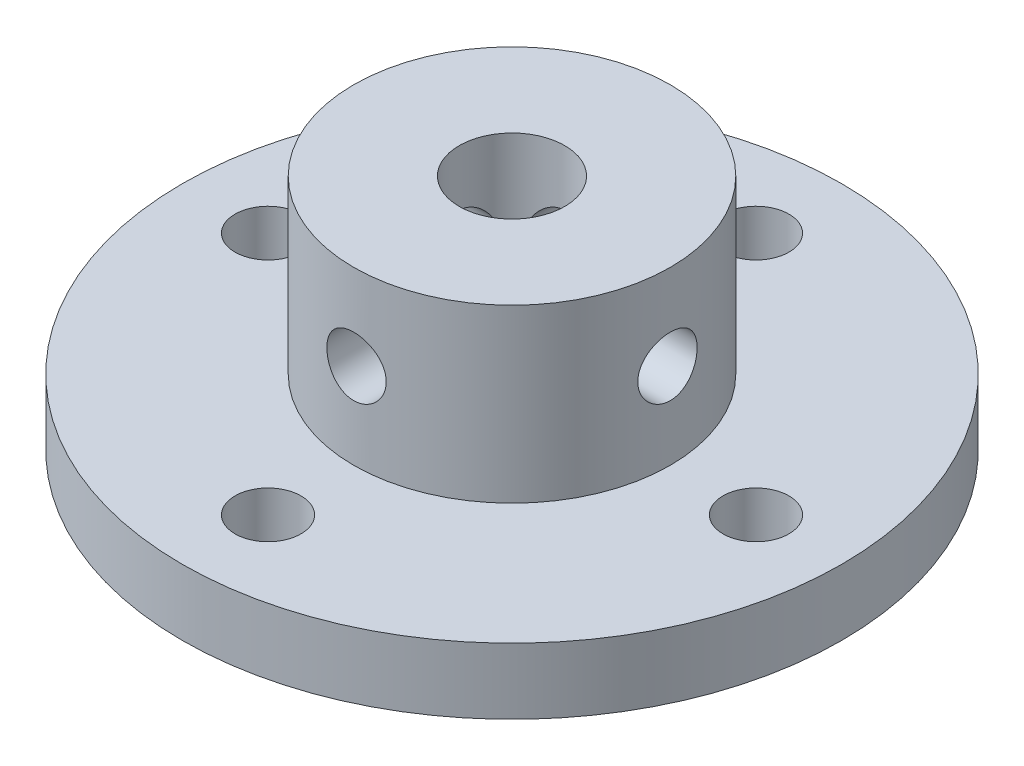
SolidWorks part; units mm, degrees
ref_plane "前视基准面" through (0, 0, 0) normal (0, 0, 1) x (1, 0, 0)
ref_plane "上视基准面" through (0, 0, 0) normal (0, 1, 0) x (1, 0, 0)
ref_plane "右视基准面" through (0, 0, 0) normal (1, 0, 0) x (0, 0, -1)
other "Configuration Table"
sketch "草图1" plane through (0, 0, 0) normal (0, 1, 0) x (1, 0, 0)
  circle A0 centre (0, 0) radius 25
  dimension "D1" = 50
extrude "凸台-拉伸1" add sketch "草图1" along normal blind 5
sketch "草图2" plane through (0, 5, 0) normal (0, 1, 0) x (1, 0, 0)
  circle A0 centre (0, 0) radius 12
  dimension "D1" = 24
extrude "凸台-拉伸2" add sketch "草图2" along normal blind 13
sketch "草图3" plane through (0, 18, 0) normal (0, 1, 0) x (1, 0, 0)
  circle A0 centre (0, 0) radius 4
  dimension "D1" = 8
extrude "切除-拉伸1" cut sketch "草图3" against normal through all
sketch "草图4" plane through (0, 5, 0) normal (0, 1, 0) x (1, 0, 0)
  circle A0 centre (0, 0) radius 18.5
  circle A1 centre (0, 18.5) radius 2.5
  circle A2 centre (18.5, 0) radius 2.5
  circle A3 centre (0, -18.5) radius 2.5
  circle A4 centre (-18.5, 0) radius 2.5
  dimension "D1" = 37
  dimension "D2" = 5
  dimension "D3" = 5
  dimension "D4" = 5
  dimension "D5" = 5
extrude "切除-拉伸2" cut sketch "草图4" against normal through all contours A0 A1 | A0 A1 | A0 A2 | A0 A2 | A0 A3 | A0 A3 | A0 A4 | A0 A4
sketch "草图5" plane through (0, 0, 0) normal (1, 0, 0) x (0, 0, -1)
  line L0 (0, 9.9) -> (0, -9.9) construction
  line L1 (12, 18) -> (-12, 18) construction
  circle A0 centre (0, 11.5) radius 2.25
  dimension "D1" = 4.5
  dimension "D2" = 6.5
extrude "切除-拉伸3" cut sketch "草图5" against normal through all and the other way through all
cosmetic thread "装饰螺纹线2" parameters "D2"=5.5
cosmetic thread "装饰螺纹线4" parameters "D2"=5.5
sketch "草图6" plane through (0, 0, 0) normal (0, 0, 1) x (1, 0, 0)
  line L0 (0, -9.9) -> (0, 9.9) construction
  line L1 (4, 18) -> (-4, 18) construction
  circle A0 centre (0, 11.5) radius 2.25
  dimension "D1" = 4.5
  dimension "D2" = 6.5
extrude "切除-拉伸4" cut sketch "草图6" against normal through all and the other way through all
cosmetic thread "装饰螺纹线1" parameters "D2"=5.5
cosmetic thread "装饰螺纹线3" parameters "D2"=5.5
